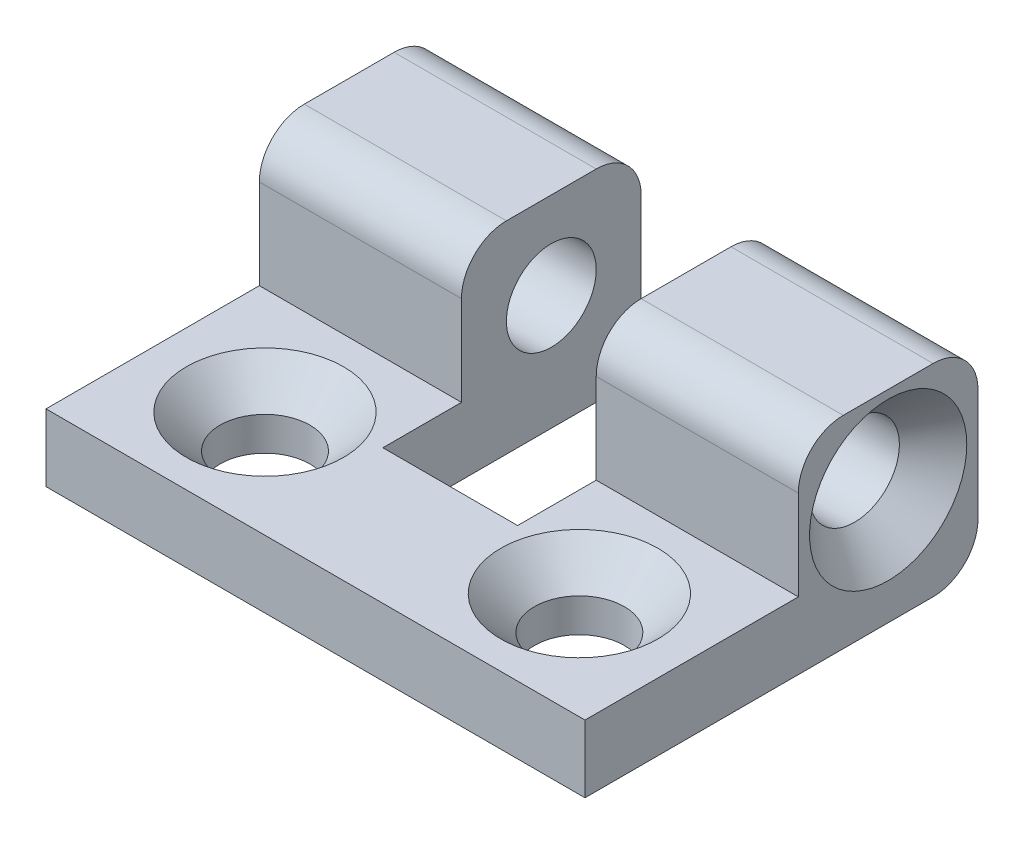
SolidWorks part; units mm, degrees
ref_plane "Plan de face" through (0, 0, 0) normal (0, 0, 1) x (1, 0, 0)
ref_plane "Plan de dessus" through (0, 0, 0) normal (0, 1, 0) x (1, 0, 0)
ref_plane "Plan de droite" through (0, 0, 0) normal (1, 0, 0) x (0, 0, -1)
sketch "Esquisse1" plane through (0, 0, 0) normal (1, 0, 0) x (0, 0, -1)
  line L0 (5.2593, 7.2778) -> (5.2593, -9.9815) construction
  line L1 (-8.2407, 1.2778) -> (1.2593, 1.2778)
  line L2 (-8.2407, 1.2778) -> (-8.2407, -1.7222)
  line L3 (-8.2407, -1.7222) -> (7.2593, -1.7222)
  line L4 (9.2593, 5.2778) -> (9.2593, 0.2778)
  line L7 (7.2593, 7.2778) -> (3.2593, 7.2778)
  line L8 (1.2593, 1.2778) -> (1.2593, 5.2778)
  circle A0 centre (5.2593, 3.4013) radius 6.5 construction
  circle A1 centre (5.2593, 3.4013) radius 2
  arc A2 (7.2593, -1.7222) -> (9.2593, 0.2778) centre (7.2593, 0.2778) ccw
  arc A3 (9.2593, 5.2778) -> (7.2593, 7.2778) centre (7.2593, 5.2778) ccw
  arc A4 (3.2593, 7.2778) -> (1.2593, 5.2778) centre (3.2593, 5.2778) ccw
  point P20 (1.2593, 7.2778)
  dimension "D3" = 13
  dimension "D4" = 4
  dimension "D7" = 2
  dimension "D1" = 3
  dimension "D2" = 8
  dimension "D5" = 17.5
  dimension "D6" = 9
extrude "Boss.-Extru.1" add sketch "Esquisse1" along normal blind 24
sketch "Esquisse2" plane through (0, 1.2778, 0) normal (0, 1, 0) x (1, 0, 0)
  line L0 (24, 9.2593) -> (0, 9.2593) construction
  line L1 (9, 9.2593) -> (15, 9.2593)
  line L2 (9, 9.2593) -> (9, -2.2407)
  line L3 (9, -2.2407) -> (15, -2.2407)
  line L4 (15, 9.2593) -> (15, -2.2407)
  line L5 (0, 5.2593) -> (24, 5.2593) construction
  line L6 (0, 7.2593) -> (0, 3.2593) construction
  line L7 (24, 7.2593) -> (24, 3.2593) construction
  line L8 (24, -8.2407) -> (0, -8.2407) construction
  line L9 (12, -8.2407) -> (12, 10.5417) construction
  line L10 (24, -3.4907) -> (0, -3.4907) construction
  line L11 (24, 1.2593) -> (24, -8.2407) construction
  line L12 (0, 1.2593) -> (0, -8.2407) construction
  circle A0 centre (19, -3.4907) radius 2
  circle A1 centre (5, -3.4907) radius 2
  dimension "D4" = 4
  dimension "D1" = 7.5
  dimension "D2" = 3
  dimension "D3" = 6
  dimension "D5" = 5
  dimension "D6" = 5
extrude "Enlèv. mat.-Extru.1" cut sketch "Esquisse2" against normal blind 24 and the other way blind 24
chamfer "Chanfrein1" distance 1.5 angle 45 3 edges at (24, 3.4013, -7.2593) (5, 1.2778, 1.4907) (19, 1.2778, 1.4907)
